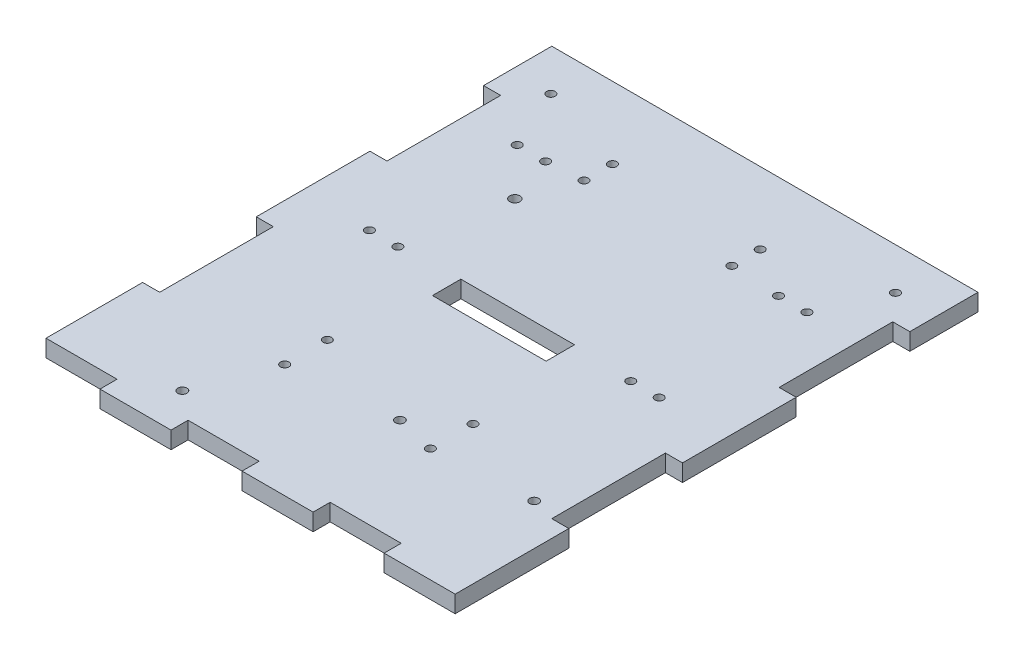
SolidWorks part; units mm, degrees
material "Pine"
ref_plane "Front Plane" through (0, 0, 0) normal (0, 0, 1) x (1, 0, 0)
ref_plane "Top Plane" through (0, 0, 0) normal (0, 1, 0) x (1, 0, 0)
ref_plane "Right Plane" through (0, 0, 0) normal (1, 0, 0) x (0, 0, -1)
sketch "Sketch1" plane through (0, 0, 0) normal (0, 1, 0) x (1, 0, 0)
  line L1 (-75, 92) -> (75, 92)
  line L2 (-75, 92) -> (-75, -92)
  line L3 (-75, -92) -> (75, -92)
  line L4 (75, 92) -> (75, -92)
  line L5 (-75, 92) -> (75, -92) construction
  line L6 (-75, -92) -> (75, 92) construction
  point P0 (0, 0)
  dimension "D1" = 150
  dimension "D2" = 184
extrude "Boss-Extrude1" add sketch "Sketch1" along normal blind 6
sketch "Sketch2" plane through (0, 6, 0) normal (0, 1, 0) x (1, 0, 0)
  line L0 (-75, 92) -> (-75, -92) construction
  line L1 (-75, 68) -> (-69, 68)
  line L2 (-75, 68) -> (-75, 28)
  line L3 (-75, 28) -> (-69, 28)
  line L4 (-69, 68) -> (-69, 28)
  line L5 (75, 92) -> (-75, 92) construction
  line L6 (69, 68) -> (69, 28)
  line L7 (69, 68) -> (75, 68)
  line L8 (75, 68) -> (75, 28)
  line L9 (69, 28) -> (75, 28)
  line L10 (69, -12) -> (69, -52)
  line L11 (69, -12) -> (75, -12)
  line L12 (75, -12) -> (75, -52)
  line L13 (69, -52) -> (75, -52)
  line L14 (-75, -12) -> (-75, -52)
  line L15 (-75, -12) -> (-69, -12)
  line L16 (-69, -12) -> (-69, -52)
  line L17 (-75, -52) -> (-69, -52)
  dimension "D1" = 24
  dimension "D2" = 40
  dimension "D3" = 6
  dimension "D4" = 2
  dimension "D5" = 2
extrude "Cut-Extrude1" cut sketch "Sketch2" against normal blind 6
sketch "Sketch6" plane through (0, 6, 0) normal (0, 1, 0) x (1, 0, 0)
  line L1 (75, -92) -> (75, -52) construction
  circle A0 centre (16, 10) radius 1.23
  dimension "D1" = 2.46
  dimension "D2" = 102
  dimension "D3" = 59
extrude "Cut-Extrude6" [suppressed] cut sketch "Sketch6" against normal through all
sketch "Sketch7" plane through (0, 6, 0) normal (0, 1, 0) x (1, 0, 0)
  line L0 (75, -92) -> (75, -52) construction
  line L1 (-75, -92) -> (75, -92) construction
  circle A0 centre (16, 55) radius 2
  dimension "D1" = 59
  dimension "D2" = 147
extrude "Cut-Extrude7" [suppressed] cut sketch "Sketch7" against normal through all
sketch "Sketch8" plane through (0, 6, 0) normal (0, 1, 0) x (1, 0, 0)
  line L0 (75, 68) -> (75, 92) construction
  line L1 (-75, -92) -> (75, -92) construction
  circle A0 centre (-16, 55) radius 2.38
  dimension "D1" = 91
  dimension "D2" = 147
extrude "Cut-Extrude8" [suppressed] cut sketch "Sketch8" against normal through all
sketch "Sketch9" plane through (0, 6, 0) normal (0, 1, 0) x (1, 0, 0)
  circle A0 centre (30.25, -1) radius 2.55
  circle A1 centre (30.25, -11) radius 2.55
  circle A2 centre (-19.25, -1) radius 2.55
  circle A3 centre (-19.25, -11) radius 2.55
  dimension "D1" = 49.5
  dimension "D2" = 0
  dimension "D3" = 10
  dimension "D4" = 0
  dimension "D5" = 49.5
  dimension "D6" = 0
  dimension "D7" = 93
  dimension "D8" = 55.75
extrude "Cut-Extrude9" [suppressed] cut sketch "Sketch9" against normal through all
sketch "Sketch11" plane through (0, 6, 0) normal (0, 1, 0) x (1, 0, 0)
  line L0 (-25, -92) -> (-25, -86)
  line L1 (-75, -92) -> (-50, -92)
  line L2 (-75, -92) -> (-75, -86)
  line L3 (-75, -86) -> (-50, -86)
  line L4 (-50, -92) -> (-50, -86)
  line L5 (-25, -92) -> (0, -92)
  line L6 (0, -92) -> (0, -86)
  line L7 (-25, -86) -> (0, -86)
  line L8 (25, -92) -> (25, -86)
  line L9 (25, -92) -> (50, -92)
  line L10 (50, -92) -> (50, -86)
  line L11 (25, -86) -> (50, -86)
  dimension "D1" = 6
  dimension "D2" = 25
  dimension "D3" = 3
extrude "Cut-Extrude10" cut sketch "Sketch11" against normal blind 6
sketch "Sketch12" plane through (0, 6, 0) normal (0, 1, 0) x (1, 0, 0)
  line L0 (-69, -52) -> (-69, -12) construction
  line L1 (0, -86) -> (-25, -86) construction
  circle A0 centre (-35, -78) radius 1.6
  dimension "D3" = 3.2
  dimension "D1" = 34
  dimension "D2" = 8
extrude "Cut-Extrude11" cut sketch "Sketch12" against normal up to next
sketch "Sketch13" plane through (0, 6, 0) normal (0, 1, 0) x (1, 0, 0)
  line L0 (-69, -52) -> (-69, -12) construction
  circle A0 centre (-35, 39) radius 1.8
  circle A1 centre (-35, -78) radius 1.6 construction
  dimension "D1" = 3.6
  dimension "D2" = 34
  dimension "D3" = 117
extrude "Cut-Extrude12" cut sketch "Sketch13" against normal up to next
sketch "Sketch14" plane through (0, 6, 0) normal (0, 1, 0) x (1, 0, 0)
  line L0 (69, -12) -> (69, -52) construction
  line L1 (50, -86) -> (25, -86) construction
  circle A0 centre (12.25, -48.7) radius 1.6
  circle A1 centre (60.5, -49.7) radius 1.6
  dimension "D2" = 3.2
  dimension "D4" = 3.2
  dimension "D1" = 8.5
  dimension "D3" = 36.3
  dimension "D5" = 37.3
  dimension "D6" = 56.75
extrude "Cut-Extrude13" cut sketch "Sketch14" against normal up to next
sketch "Sketch15" plane through (0, 6, 0) normal (0, 1, 0) x (1, 0, 0)
  line L1 (-20, 5) -> (20, 5)
  line L2 (-20, 5) -> (-20, -5)
  line L3 (-20, -5) -> (20, -5)
  line L4 (20, 5) -> (20, -5)
  line L5 (-20, 5) -> (20, -5) construction
  line L6 (-20, -5) -> (20, 5) construction
  point P0 (0, 0)
  dimension "D1" = 40
  dimension "D2" = 10
extrude "Cut-Extrude14" cut sketch "Sketch15" against normal up to next
extrude "Cut-Extrude15" cut sketch "Sketch16" against normal blind 6
sketch "Sketch16" plane through (0, 0, 0) normal (0, -1, 0) x (1, 0, 0)
  circle A0 centre (60.6475, -77.3069) radius 1.5
  circle A1 centre (50.9845, -55.8033) radius 1.5
  circle A2 centre (40.9845, -55.8033) radius 1.5
  circle A4 centre (50.9845, -3.8033) radius 1.5
  circle A5 centre (40.9845, -3.8033) radius 1.5
  circle A6 centre (26.2761, 37) radius 1.5
  circle A7 centre (26.2761, 52) radius 1.5
  circle A8 centre (-25, 52) radius 1.5
  circle A9 centre (-25, 37) radius 1.5
  circle A10 centre (-40.9845, -3.8033) radius 1.5
  circle A11 centre (-50.9845, -3.8033) radius 1.5
  circle A12 centre (-40.9845, -55.8033) radius 1.5
  circle A13 centre (-50.9845, -55.8033) radius 1.5
  circle A14 centre (-60.6475, -77.3069) radius 1.5
extrude "Cut-Extrude16" cut sketch "Sketch17" against normal blind 6
sketch "Sketch17" plane through (0, 6, 0) normal (0, 1, 0) x (1, 0, 0)
  circle A0 centre (-28.3884, 66.7308) radius 1.5
  circle A1 centre (-28.3884, 56.7308) radius 1.5
  circle A2 centre (23.6116, 56.7308) radius 1.5
  circle A3 centre (23.6116, 66.7308) radius 1.5
extrude "Cut-Extrude17" cut sketch "Sketch18" against normal blind 7.5 and the other way through all
sketch "Sketch18" plane through (0, -2, 0) normal (0, -1, 0) x (-1, 0, 0)
  circle A0 centre (11.5, 34.1846) radius 1.5
  circle A1 centre (-11.5, 34.1846) radius 1.5
